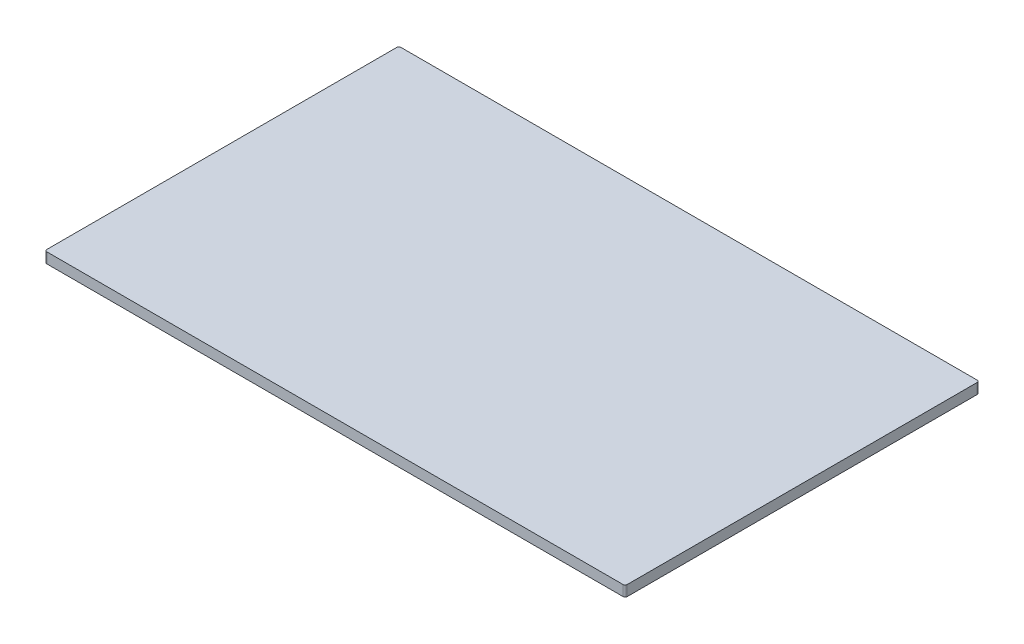
SolidWorks part; units mm, degrees
ref_plane "Front Plane" through (0, 0, 0) normal (0, 0, 1) x (1, 0, 0)
ref_plane "Top Plane" through (0, 0, 0) normal (0, 1, 0) x (1, 0, 0)
ref_plane "Right Plane" through (0, 0, 0) normal (1, 0, 0) x (0, 0, -1)
sketch "Sketch1" plane through (0, 0, 0) normal (0, 1, 0) x (1, 0, 0)
  line L1 (270, -162) -> (-270, -162) construction
  line L2 (270, -162) -> (270, 162) construction
  line L3 (270, 162) -> (-270, 162) construction
  line L4 (-270, -162) -> (-270, 162) construction
  line L5 (270, -162) -> (-270, 162) construction
  line L6 (270, 162) -> (-270, -162) construction
  line L7 (277, -169) -> (-277, -169)
  line L8 (277, -169) -> (277, 169)
  line L9 (277, 169) -> (-277, 169)
  line L10 (-277, -169) -> (-277, 169)
  line L11 (277, -169) -> (-277, 169) construction
  line L12 (277, 169) -> (-277, -169) construction
  point P0 (0, 0)
  point P6 (0, 0)
  dimension "D1" = 7
  dimension "D2" = 7
  dimension "D3" = 540
  dimension "D4" = 324
extrude "Boss-Extrude1" add sketch "Sketch1" along normal blind 10
fillet "Fillet1" radius 2 4 edges at (-277, 5, -169) (277, 5, -169) (277, 5, 169) (-277, 5, 169)
